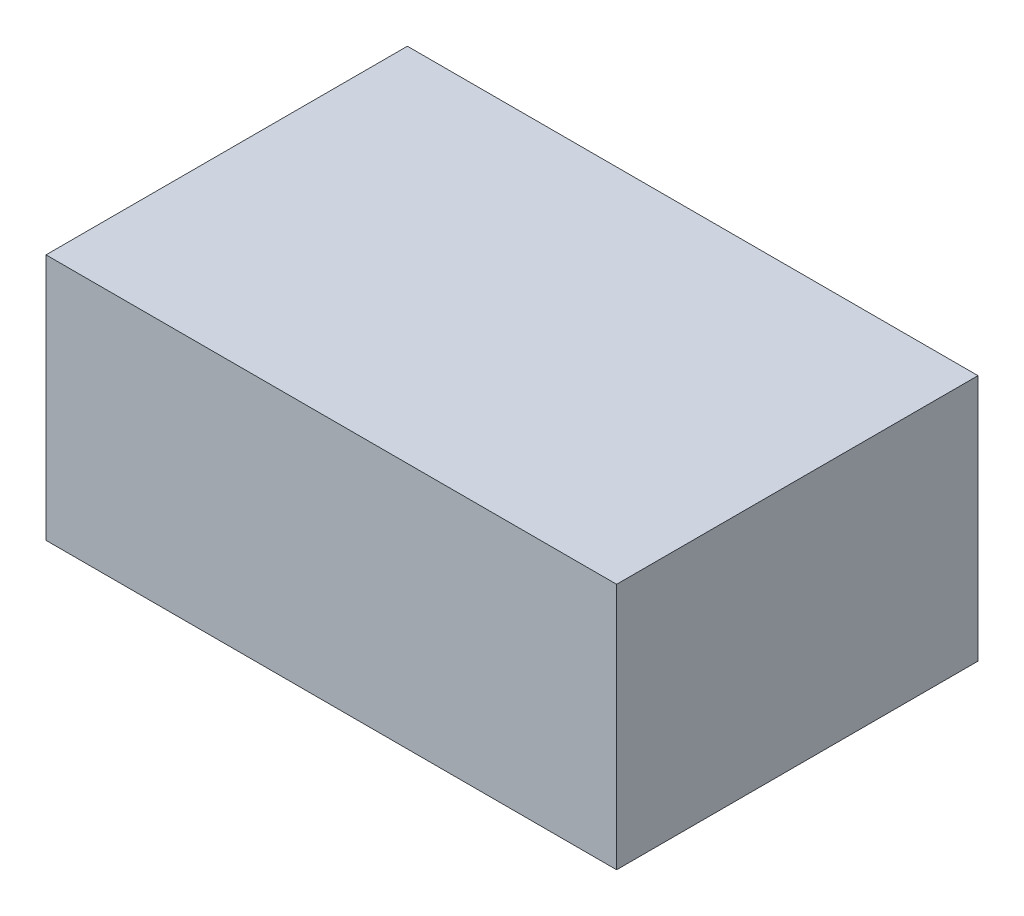
SolidWorks part; units mm, degrees
ref_plane "前视基准面" through (0, 0, 0) normal (0, 0, 1) x (1, 0, 0)
ref_plane "上视基准面" through (0, 0, 0) normal (0, 1, 0) x (1, 0, 0)
ref_plane "右视基准面" through (0, 0, 0) normal (1, 0, 0) x (0, 0, -1)
sketch "草图1" plane through (0, 0, 0) normal (0, 0, 1) x (1, 0, 0)
  line L1 (-66.8924, 34.5673) -> (83.1076, 34.5673)
  line L2 (-66.8924, 34.5673) -> (-66.8924, -30.4327)
  line L3 (-66.8924, -30.4327) -> (83.1076, -30.4327)
  line L4 (83.1076, 34.5673) -> (83.1076, -30.4327)
  dimension "D1" = 150
  dimension "D2" = 65
extrude "凸台-拉伸1" add sketch "草图1" along normal blind 95
